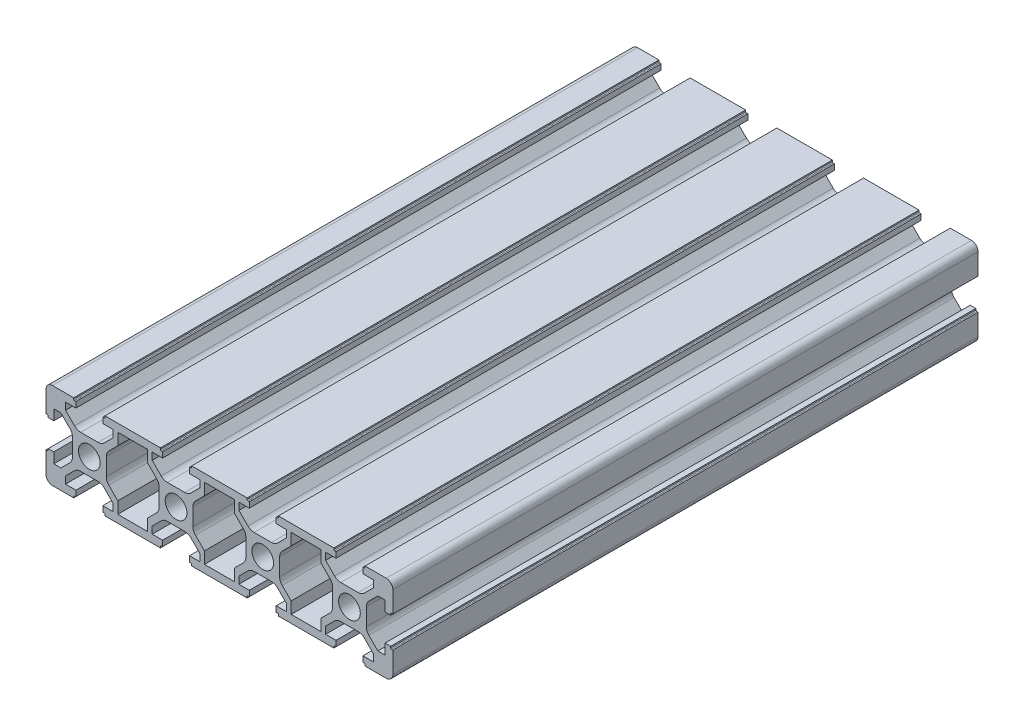
SolidWorks part; units mm, degrees
material "6063-T5"
ref_plane "Front Plane" through (0, 0, 0) normal (0, 0, 1) x (1, 0, 0)
ref_plane "Top Plane" through (0, 0, 0) normal (0, 1, 0) x (1, 0, 0)
ref_plane "Right Plane" through (0, 0, 0) normal (1, 0, 0) x (0, 0, -1)
sketch "Sketch2" plane through (0, 0, 0) normal (0, 0, 1) x (1, 0, 0)
  line L1 (-40, -10) -> (40, -10)
  line L2 (-40, -10) -> (-40, 10)
  line L3 (-40, 10) -> (40, 10)
  line L4 (40, -10) -> (40, 10)
  line L5 (-40, -10) -> (40, 10) construction
  line L6 (-40, 10) -> (40, -10) construction
  point P0 (0, 0)
  dimension "D1" = 80
  dimension "D2" = 20
extrude "Boss-Extrude1" add sketch "Sketch2" against normal mid plane 135
sketch "Sketch3" plane through (0, 0, 67.5) normal (0, 0, 1) x (1, 0, 0)
  line L0 (-10, -998.1953) -> (-10, 49001.8047) construction
  line L1 (0, -1000) -> (0, 49000) construction
  line L2 (10, -998.6632) -> (10, 49001.3368) construction
  line L3 (-1000, 0) -> (49000, 0) construction
  line L4 (-13.6, 10) -> (-6.4, 10)
  line L5 (-6.4, 10) -> (-6.4, 9.7)
  line L6 (-6.6, 9.5) -> (-6.9, 9.5)
  line L7 (-6.9, 9.5) -> (-6.9, 8.2)
  line L8 (-6.9, 8.2) -> (-4.5, 8.2)
  line L9 (-4.5, 8.2) -> (-4.5, 6.5607)
  line L10 (-4.5, 6.5607) -> (-6.5749, 4.4858)
  line L11 (-12.0109, 3.9) -> (-7.9891, 3.9)
  line L12 (-13.4251, 4.4858) -> (-15.5, 6.5607)
  line L13 (-15.5, 6.5607) -> (-15.5, 8.2)
  line L14 (-15.5, 8.2) -> (-13.1, 8.2)
  line L15 (-13.1, 8.2) -> (-13.1, 9.5)
  line L16 (-13.1, 9.5) -> (-13.4, 9.5)
  line L17 (-13.6, 10) -> (-13.6, 9.7)
  line L18 (40, 10) -> (-40, 10) construction
  line L19 (-717.1068, -707.1068) -> (34638.2323, 34648.2323) construction
  line L20 (-10, 10) -> (-10, 0) construction
  line L21 (-13.6, -10) -> (-13.6, -9.7)
  line L22 (-13.6, -10) -> (-6.4, -10)
  line L23 (-6.4, -10) -> (-6.4, -9.7)
  line L24 (-6.6, -9.5) -> (-6.9, -9.5)
  line L25 (-6.9, -9.5) -> (-6.9, -8.2)
  line L26 (-6.9, -8.2) -> (-4.5, -8.2)
  line L27 (-4.5, -8.2) -> (-4.5, -6.5607)
  line L28 (-4.5, -6.5607) -> (-6.5749, -4.4858)
  line L29 (-12.0109, -3.9) -> (-7.9891, -3.9)
  line L30 (-13.4251, -4.4858) -> (-15.5, -6.5607)
  line L31 (-15.5, -6.5607) -> (-15.5, -8.2)
  line L32 (-15.5, -8.2) -> (-13.1, -8.2)
  line L33 (-13.1, -8.2) -> (-13.1, -9.5)
  line L34 (-13.1, -9.5) -> (-13.4, -9.5)
  line L35 (13.6, -10) -> (6.4, -10)
  line L36 (6.4, -10) -> (6.4, -9.7)
  line L37 (6.6, -9.5) -> (6.9, -9.5)
  line L38 (6.9, -9.5) -> (6.9, -8.2)
  line L39 (6.9, -8.2) -> (4.5, -8.2)
  line L40 (4.5, -8.2) -> (4.5, -6.5607)
  line L41 (4.5, -6.5607) -> (6.5749, -4.4858)
  line L42 (12.0109, -3.9) -> (7.9891, -3.9)
  line L43 (13.4251, -4.4858) -> (15.5, -6.5607)
  line L44 (15.5, -6.5607) -> (15.5, -8.2)
  line L45 (15.5, -8.2) -> (13.1, -8.2)
  line L46 (13.1, -8.2) -> (13.1, -9.5)
  line L47 (13.1, -9.5) -> (13.4, -9.5)
  line L48 (13.6, -10) -> (13.6, -9.7)
  line L49 (13.6, 10) -> (13.6, 9.7)
  line L50 (13.6, 10) -> (6.4, 10)
  line L51 (6.4, 10) -> (6.4, 9.7)
  line L52 (6.6, 9.5) -> (6.9, 9.5)
  line L53 (6.9, 9.5) -> (6.9, 8.2)
  line L54 (6.9, 8.2) -> (4.5, 8.2)
  line L55 (4.5, 8.2) -> (4.5, 6.5607)
  line L56 (4.5, 6.5607) -> (6.5749, 4.4858)
  line L57 (12.0109, 3.9) -> (7.9891, 3.9)
  line L58 (13.4251, 4.4858) -> (15.5, 6.5607)
  line L59 (15.5, 6.5607) -> (15.5, 8.2)
  line L60 (15.5, 8.2) -> (13.1, 8.2)
  line L61 (13.1, 8.2) -> (13.1, 9.5)
  line L62 (13.1, 9.5) -> (13.4, 9.5)
  line L77 (-36.5607, -5.5) -> (-38.2, -5.5)
  line L78 (-36.5607, 5.5) -> (-34.4858, 3.4251)
  line L79 (-38.2, 3.1) -> (-38.2, 5.5)
  line L80 (-39.5, 3.4) -> (-39.5, 3.1)
  line L81 (-39.5, -3.1) -> (-39.5, -3.4)
  line L82 (-38.2, -5.5) -> (-38.2, -3.1)
  line L83 (-34.4858, -3.4251) -> (-36.5607, -5.5)
  line L84 (-33.9, -2.0109) -> (-33.9, 2.0109)
  line L85 (-40, -3.6) -> (-39.7, -3.6)
  line L86 (-38.2, 5.5) -> (-36.5607, 5.5)
  line L87 (-39.5, 3.1) -> (-38.2, 3.1)
  line L88 (-40, 3.6) -> (-39.7, 3.6)
  line L89 (-38.2, -3.1) -> (-39.5, -3.1)
  line L90 (-40, -3.6) -> (-40, 3.6)
  line L91 (-40, 10) -> (-40, -10) construction
  line L92 (34.4858, -3.4251) -> (36.5607, -5.5)
  line L93 (33.9, -2.0109) -> (33.9, 2.0109)
  line L94 (36.5607, 5.5) -> (34.4858, 3.4251)
  line L95 (38.2, 5.5) -> (36.5607, 5.5)
  line L96 (38.2, 3.1) -> (38.2, 5.5)
  line L97 (39.5, 3.1) -> (38.2, 3.1)
  line L98 (39.5, 3.4) -> (39.5, 3.1)
  line L99 (40, 3.6) -> (39.7, 3.6)
  line L100 (40, -3.6) -> (40, 3.6)
  line L101 (40, -3.6) -> (39.7, -3.6)
  line L102 (39.5, -3.1) -> (39.5, -3.4)
  line L103 (38.2, -3.1) -> (39.5, -3.1)
  line L104 (38.2, -5.5) -> (38.2, -3.1)
  line L105 (36.5607, -5.5) -> (38.2, -5.5)
  line L148 (-3.4393, 8.2) -> (-3.4393, 5.5)
  line L149 (-3.4393, 5.5) -> (-5.5142, 3.4251)
  line L150 (-3.4393, 8.2) -> (3.4393, 8.2)
  line L151 (3.4393, 8.2) -> (3.4393, 5.5)
  line L152 (3.4393, 5.5) -> (5.5142, 3.4251)
  line L153 (6.1, 2.0109) -> (6.1, -2.0109)
  line L154 (5.5142, -3.4251) -> (3.4393, -5.5)
  line L155 (3.4393, -5.5) -> (3.4393, -8.2)
  line L156 (3.4393, -8.2) -> (-3.4393, -8.2)
  line L157 (-3.4393, -8.2) -> (-3.4393, -5.5)
  line L158 (-3.4393, -5.5) -> (-5.5142, -3.4251)
  line L159 (-6.1, 2.0109) -> (-6.1, -2.0109)
  line L160 (-30, -1000) -> (-30, 49000) construction
  line L161 (30, -1000) -> (30, 49000) construction
  line L162 (-20, -1000) -> (-20, 49000) construction
  line L163 (20, -1000) -> (20, 49000) construction
  line L206 (-26.4, 10) -> (-26.4, 9.7)
  line L207 (-26.4, 10) -> (-33.6, 10)
  line L208 (-33.6, 10) -> (-33.6, 9.7)
  line L209 (-33.4, 9.5) -> (-33.1, 9.5)
  line L210 (-33.1, 9.5) -> (-33.1, 8.2)
  line L211 (-33.1, 8.2) -> (-35.5, 8.2)
  line L212 (-35.5, 8.2) -> (-35.5, 6.5607)
  line L213 (-35.5, 6.5607) -> (-33.4251, 4.4858)
  line L214 (-27.9891, 3.9) -> (-32.0109, 3.9)
  line L215 (-26.5749, 4.4858) -> (-24.5, 6.5607)
  line L216 (-24.5, 6.5607) -> (-24.5, 8.2)
  line L217 (-24.5, 8.2) -> (-26.9, 8.2)
  line L218 (-26.9, 8.2) -> (-26.9, 9.5)
  line L219 (-26.9, 9.5) -> (-26.6, 9.5)
  line L220 (-26.4, -10) -> (-33.6, -10)
  line L221 (-33.6, -10) -> (-33.6, -9.7)
  line L222 (-33.4, -9.5) -> (-33.1, -9.5)
  line L223 (-33.1, -9.5) -> (-33.1, -8.2)
  line L224 (-33.1, -8.2) -> (-35.5, -8.2)
  line L225 (-35.5, -8.2) -> (-35.5, -6.5607)
  line L226 (-35.5, -6.5607) -> (-33.4251, -4.4858)
  line L227 (-27.9891, -3.9) -> (-32.0109, -3.9)
  line L228 (-26.5749, -4.4858) -> (-24.5, -6.5607)
  line L229 (-24.5, -6.5607) -> (-24.5, -8.2)
  line L230 (-24.5, -8.2) -> (-26.9, -8.2)
  line L231 (-26.9, -8.2) -> (-26.9, -9.5)
  line L232 (-26.9, -9.5) -> (-26.6, -9.5)
  line L233 (-26.4, -10) -> (-26.4, -9.7)
  line L234 (26.4, 10) -> (33.6, 10)
  line L235 (33.6, 10) -> (33.6, 9.7)
  line L236 (33.4, 9.5) -> (33.1, 9.5)
  line L237 (33.1, 9.5) -> (33.1, 8.2)
  line L238 (33.1, 8.2) -> (35.5, 8.2)
  line L239 (35.5, 8.2) -> (35.5, 6.5607)
  line L240 (35.5, 6.5607) -> (33.4251, 4.4858)
  line L241 (27.9891, 3.9) -> (32.0109, 3.9)
  line L242 (26.5749, 4.4858) -> (24.5, 6.5607)
  line L243 (24.5, 6.5607) -> (24.5, 8.2)
  line L244 (24.5, 8.2) -> (26.9, 8.2)
  line L245 (26.9, 8.2) -> (26.9, 9.5)
  line L246 (26.9, 9.5) -> (26.6, 9.5)
  line L247 (26.4, 10) -> (26.4, 9.7)
  line L248 (26.4, -10) -> (26.4, -9.7)
  line L249 (26.9, -9.5) -> (26.6, -9.5)
  line L250 (26.9, -8.2) -> (26.9, -9.5)
  line L251 (24.5, -8.2) -> (26.9, -8.2)
  line L252 (24.5, -6.5607) -> (24.5, -8.2)
  line L253 (26.5749, -4.4858) -> (24.5, -6.5607)
  line L254 (27.9891, -3.9) -> (32.0109, -3.9)
  line L255 (35.5, -6.5607) -> (33.4251, -4.4858)
  line L256 (35.5, -8.2) -> (35.5, -6.5607)
  line L257 (33.1, -8.2) -> (35.5, -8.2)
  line L258 (33.1, -9.5) -> (33.1, -8.2)
  line L259 (33.4, -9.5) -> (33.1, -9.5)
  line L260 (33.6, -10) -> (33.6, -9.7)
  line L261 (26.4, -10) -> (33.6, -10)
  line L262 (-16.5607, -5.5) -> (-14.4858, -3.4251)
  line L263 (-16.5607, -8.2) -> (-16.5607, -5.5)
  line L264 (-23.4393, -8.2) -> (-16.5607, -8.2)
  line L265 (-23.4393, -5.5) -> (-23.4393, -8.2)
  line L266 (-25.5142, -3.4251) -> (-23.4393, -5.5)
  line L267 (-26.1, 2.0109) -> (-26.1, -2.0109)
  line L268 (-23.4393, 5.5) -> (-25.5142, 3.4251)
  line L269 (-23.4393, 8.2) -> (-23.4393, 5.5)
  line L270 (-16.5607, 8.2) -> (-23.4393, 8.2)
  line L271 (-16.5607, 8.2) -> (-16.5607, 5.5)
  line L272 (-16.5607, 5.5) -> (-14.4858, 3.4251)
  line L273 (-13.9, 2.0109) -> (-13.9, -2.0109)
  line L274 (23.4393, -5.5) -> (25.5142, -3.4251)
  line L275 (23.4393, -8.2) -> (23.4393, -5.5)
  line L276 (16.5607, -8.2) -> (23.4393, -8.2)
  line L277 (16.5607, -5.5) -> (16.5607, -8.2)
  line L278 (14.4858, -3.4251) -> (16.5607, -5.5)
  line L279 (13.9, 2.0109) -> (13.9, -2.0109)
  line L280 (16.5607, 5.5) -> (14.4858, 3.4251)
  line L281 (16.5607, 8.2) -> (16.5607, 5.5)
  line L282 (23.4393, 8.2) -> (16.5607, 8.2)
  line L283 (23.4393, 8.2) -> (23.4393, 5.5)
  line L284 (23.4393, 5.5) -> (25.5142, 3.4251)
  line L285 (26.1, 2.0109) -> (26.1, -2.0109)
  arc A0 (-13.4251, 4.4858) -> (-12.0109, 3.9) centre (-12.0109, 5.9) ccw
  arc A1 (-7.9891, 3.9) -> (-6.5749, 4.4858) centre (-7.9891, 5.9) ccw
  arc A2 (-6.6, 9.5) -> (-6.4, 9.7) centre (-6.6, 9.7) ccw
  arc A4 (-13.6, 9.7) -> (-13.4, 9.5) centre (-13.4, 9.7) ccw
  circle A5 centre (-10, 0) radius 2.5
  arc A7 (-6.6, -9.5) -> (-6.4, -9.7) centre (-6.6, -9.7) cw
  arc A8 (-7.9891, -3.9) -> (-6.5749, -4.4858) centre (-7.9891, -5.9) cw
  arc A9 (-13.4251, -4.4858) -> (-12.0109, -3.9) centre (-12.0109, -5.9) cw
  arc A10 (-13.6, -9.7) -> (-13.4, -9.5) centre (-13.4, -9.7) cw
  arc A11 (6.6, -9.5) -> (6.4, -9.7) centre (6.6, -9.7) ccw
  arc A12 (7.9891, -3.9) -> (6.5749, -4.4858) centre (7.9891, -5.9) ccw
  arc A13 (13.4251, -4.4858) -> (12.0109, -3.9) centre (12.0109, -5.9) ccw
  arc A14 (13.6, -9.7) -> (13.4, -9.5) centre (13.4, -9.7) ccw
  circle A15 centre (10, 0) radius 2.5
  arc A16 (6.6, 9.5) -> (6.4, 9.7) centre (6.6, 9.7) cw
  arc A17 (7.9891, 3.9) -> (6.5749, 4.4858) centre (7.9891, 5.9) cw
  arc A18 (13.4251, 4.4858) -> (12.0109, 3.9) centre (12.0109, 5.9) cw
  arc A19 (13.6, 9.7) -> (13.4, 9.5) centre (13.4, 9.7) cw
  arc A24 (-39.5, 3.4) -> (-39.7, 3.6) centre (-39.7, 3.4) ccw
  arc A25 (-34.4858, -3.4251) -> (-33.9, -2.0109) centre (-35.9, -2.0109) ccw
  arc A26 (-33.9, 2.0109) -> (-34.4858, 3.4251) centre (-35.9, 2.0109) ccw
  arc A27 (-39.7, -3.6) -> (-39.5, -3.4) centre (-39.7, -3.4) ccw
  arc A28 (34.4858, -3.4251) -> (33.9, -2.0109) centre (35.9, -2.0109) cw
  arc A29 (33.9, 2.0109) -> (34.4858, 3.4251) centre (35.9, 2.0109) cw
  arc A30 (39.5, 3.4) -> (39.7, 3.6) centre (39.7, 3.4) cw
  arc A31 (39.7, -3.6) -> (39.5, -3.4) centre (39.7, -3.4) cw
  arc A33 (-5.5142, 3.4251) -> (-6.1, 2.0109) centre (-4.1, 2.0109) ccw
  arc A35 (5.5142, 3.4251) -> (6.1, 2.0109) centre (4.1, 2.0109) cw
  arc A37 (6.1, -2.0109) -> (5.5142, -3.4251) centre (4.1, -2.0109) cw
  arc A39 (-5.5142, -3.4251) -> (-6.1, -2.0109) centre (-4.1, -2.0109) cw
  circle A40 centre (-30, 0) radius 2.5
  circle A41 centre (30, 0) radius 2.5
  arc A54 (-33.4, 9.5) -> (-33.6, 9.7) centre (-33.4, 9.7) cw
  arc A55 (-32.0109, 3.9) -> (-33.4251, 4.4858) centre (-32.0109, 5.9) cw
  arc A56 (-26.5749, 4.4858) -> (-27.9891, 3.9) centre (-27.9891, 5.9) cw
  arc A57 (-26.4, 9.7) -> (-26.6, 9.5) centre (-26.6, 9.7) cw
  arc A58 (-33.4, -9.5) -> (-33.6, -9.7) centre (-33.4, -9.7) ccw
  arc A59 (-32.0109, -3.9) -> (-33.4251, -4.4858) centre (-32.0109, -5.9) ccw
  arc A60 (-26.5749, -4.4858) -> (-27.9891, -3.9) centre (-27.9891, -5.9) ccw
  arc A61 (-26.4, -9.7) -> (-26.6, -9.5) centre (-26.6, -9.7) ccw
  arc A62 (33.4, 9.5) -> (33.6, 9.7) centre (33.4, 9.7) ccw
  arc A63 (32.0109, 3.9) -> (33.4251, 4.4858) centre (32.0109, 5.9) ccw
  arc A64 (26.5749, 4.4858) -> (27.9891, 3.9) centre (27.9891, 5.9) ccw
  arc A65 (26.4, 9.7) -> (26.6, 9.5) centre (26.6, 9.7) ccw
  arc A66 (26.4, -9.7) -> (26.6, -9.5) centre (26.6, -9.7) cw
  arc A67 (26.5749, -4.4858) -> (27.9891, -3.9) centre (27.9891, -5.9) cw
  arc A68 (32.0109, -3.9) -> (33.4251, -4.4858) centre (32.0109, -5.9) cw
  arc A69 (33.4, -9.5) -> (33.6, -9.7) centre (33.4, -9.7) cw
  arc A70 (-26.1, -2.0109) -> (-25.5142, -3.4251) centre (-24.1, -2.0109) ccw
  arc A71 (-25.5142, 3.4251) -> (-26.1, 2.0109) centre (-24.1, 2.0109) ccw
  arc A72 (-14.4858, 3.4251) -> (-13.9, 2.0109) centre (-15.9, 2.0109) cw
  arc A73 (-14.4858, -3.4251) -> (-13.9, -2.0109) centre (-15.9, -2.0109) ccw
  arc A74 (13.9, -2.0109) -> (14.4858, -3.4251) centre (15.9, -2.0109) ccw
  arc A75 (14.4858, 3.4251) -> (13.9, 2.0109) centre (15.9, 2.0109) ccw
  arc A76 (25.5142, 3.4251) -> (26.1, 2.0109) centre (24.1, 2.0109) cw
  arc A77 (25.5142, -3.4251) -> (26.1, -2.0109) centre (24.1, -2.0109) ccw
  dimension "D7" = 45
  dimension "D11" = 0.2
  dimension "D12" = 2
  dimension "D13" = 5
  dimension "D21" = 2
  dimension "D22" = 0.2
  dimension "D23" = 2
  dimension "D1" = 20
  dimension "D2" = 10
  dimension "D3" = 6.2
  dimension "D4" = 7.2
  dimension "D5" = 1.8
  dimension "D6" = 6.1
  dimension "D8" = 11
  dimension "D9" = 0.75
  dimension "D10" = 0.5
  dimension "D14" = 7.2
  dimension "D15" = 0.5
  dimension "D16" = 6.1
  dimension "D17" = 1.8
  dimension "D18" = 6.2
  dimension "D19" = 11
  dimension "D20" = 20
  dimension "D24" = 0.75
  dimension "D25" = 1.5
  dimension "D26" = 20
  dimension "D27" = 10
  dimension "D28" = 10
extrude "Cut-Extrude1" cut sketch "Sketch3" against normal through all both
fillet "Fillet1" radius 1.5 4 edges at (-40, -10, 0) (-40, 10, 0) (40, -10, 0) (40, 10, 0)
